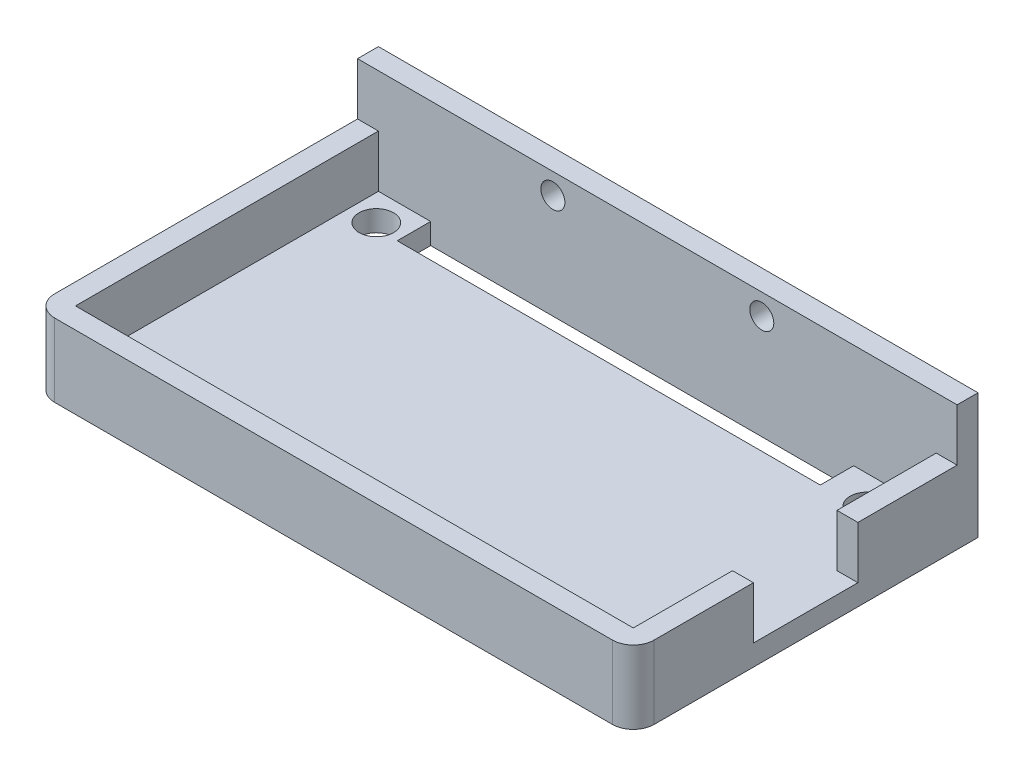
SolidWorks part; units mm, degrees
ref_plane "Front Plane" through (0, 0, 0) normal (0, 0, 1) x (1, 0, 0)
ref_plane "Top Plane" through (0, 0, 0) normal (0, 1, 0) x (1, 0, 0)
ref_plane "Right Plane" through (0, 0, 0) normal (1, 0, 0) x (0, 0, -1)
sketch "Sketch1" plane through (0, 0, 0) normal (0, 1, 0) x (1, 0, 0)
  line L1 (0, 0) -> (57.4, 0)
  line L2 (0, 0) -> (0, 33)
  line L3 (0, 33) -> (57.4, 33)
  line L4 (57.4, 0) -> (57.4, 33)
  dimension "D1" = 57.4
  dimension "D2" = 33
extrude "Boss-Extrude1" add sketch "Sketch1" along normal blind 7
shell "Shell3" thickness 2
sketch "Sketch2" plane through (0, 2, 0) normal (0, 1, 0) x (1, 0, 0)
  line L0 (4.5, 28.3) -> (4.5, 4.7) construction
  line L1 (2, 2) -> (2, 31) construction
  line L2 (2, 31) -> (2, 2) construction
  circle A0 centre (4.5, 28.3) radius 1.65
  circle A1 centre (51.5, 28.3) radius 1.65
  circle A2 centre (4.5, 4.7) radius 1.65
  circle A3 centre (51.5, 4.7) radius 1.65
  point P10 (2, 16.5)
  point P11 (4.5, 16.5)
  dimension "D1" = 3.3
  dimension "D2" = 47
  dimension "D3" = 23.6
  dimension "D4" = 2.5
extrude "Cut-Extrude1" cut sketch "Sketch2" against normal through all
sketch "Sketch3" plane through (0, 2, 0) normal (0, 1, 0) x (1, 0, 0)
  line L0 (55.4, 31) -> (2, 31) construction
  line L1 (7, 31) -> (47.5, 31)
  line L2 (7, 31) -> (7, 27.8)
  line L3 (7, 27.8) -> (47.5, 27.8)
  line L4 (47.5, 31) -> (47.5, 27.8)
  line L5 (2, 31) -> (2, 2) construction
  line L6 (2, 16.5) -> (55.4, 16.5) construction
  line L7 (55.4, 2) -> (55.4, 31) construction
  line L8 (47.5, 2) -> (47.5, 5.2)
  line L9 (7, 5.2) -> (47.5, 5.2)
  line L10 (7, 2) -> (7, 5.2)
  line L11 (7, 2) -> (47.5, 2)
  circle A0 centre (51.5, 28.3) radius 1.65 construction
  dimension "D1" = 5
  dimension "D2" = 4
  dimension "D3" = 3.2
extrude "Cut-Extrude2" cut sketch "Sketch3" against normal through all
sketch "Sketch4" plane through (0, 7, 0) normal (0, 1, 0) x (1, 0, 0)
  line L0 (55.4, 2) -> (55.4, 31) construction
  line L1 (55.4, 21.5) -> (57.4, 21.5)
  line L2 (55.4, 21.5) -> (55.4, 11.5)
  line L3 (55.4, 11.5) -> (57.4, 11.5)
  line L4 (57.4, 21.5) -> (57.4, 11.5)
  line L5 (57.4, 0) -> (57.4, 33) construction
  point P8 (57.4, 16.5)
  point P9 (57.4, 16.5)
  dimension "D1" = 10
extrude "Cut-Extrude3" cut sketch "Sketch4" against normal up to surface (5 mm away) up to face at (51.5, 2, -26.65)
sketch "Sketch5" plane through (0, 7, 0) normal (0, 1, 0) x (1, 0, 0)
  line L0 (57.4, 21.5) -> (57.4, 33) construction
  line L1 (0, 33) -> (57.4, 33)
  line L2 (0, 33) -> (0, 31)
  line L3 (0, 31) -> (57.4, 31)
  line L4 (57.4, 33) -> (57.4, 31)
  line L5 (55.4, 31) -> (47.5, 31) construction
extrude "Boss-Extrude2" add sketch "Sketch5" along normal blind 5
sketch "Sketch6" plane through (0, 0, -33) normal (0, 0, -1) x (-1, 0, 0)
  line L0 (-38.7, 10) -> (-18.7, 10) construction
  line L3 (-57.4, 12) -> (0, 12) construction
  circle A0 centre (-38.7, 10) radius 1.15
  circle A1 centre (-18.7, 10) radius 1.15
  point P5 (-28.7, 10)
  point P6 (-18.7, 7.5588)
  point P8 (-28.7, 12)
  dimension "D1" = 2.3
  dimension "D2" = 2.3
  dimension "D3" = 2
  dimension "D4" = 20
extrude "Cut-Extrude4" cut sketch "Sketch6" against normal up to next
fillet "Fillet1" radius 2 2 edges at (0, 3.5, 0) (57.4, 3.5, 0)
